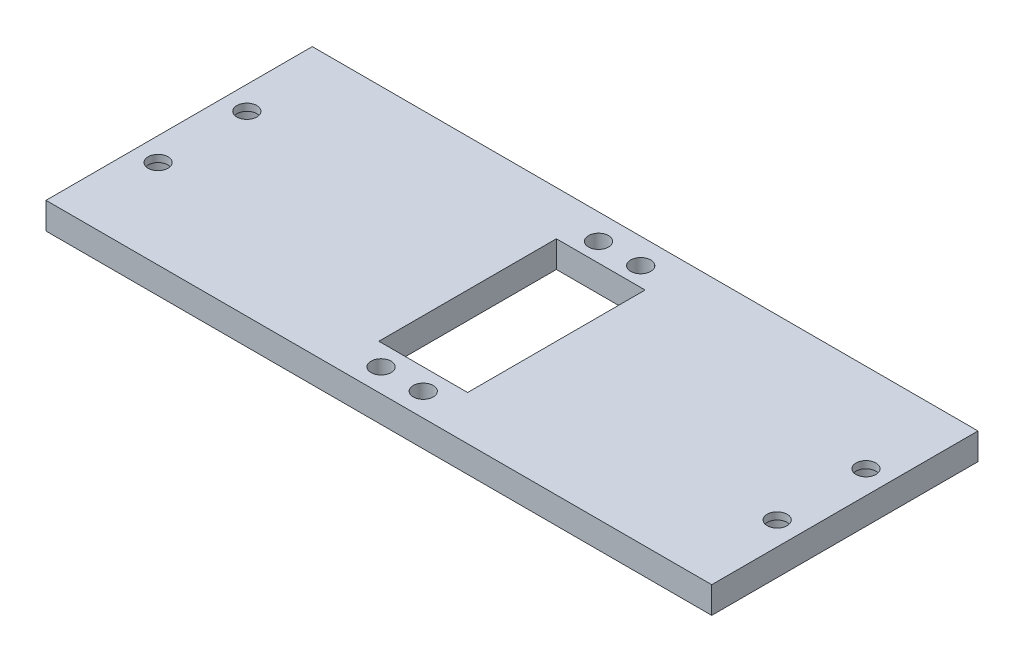
SolidWorks part; units mm, degrees
ref_plane "Front Plane" through (0, 0, 0) normal (0, 0, 1) x (1, 0, 0)
ref_plane "Top Plane" through (0, 0, 0) normal (0, 1, 0) x (1, 0, 0)
ref_plane "Right Plane" through (0, 0, 0) normal (1, 0, 0) x (0, 0, -1)
sketch "Sketch1" plane through (0, 0, 0) normal (0, 1, 0) x (1, 0, 0)
  line L0 (75, -30) -> (-75, -30)
  line L1 (75, -30) -> (75, 30)
  line L2 (75, 30) -> (-75, 30)
  line L3 (-75, -30) -> (-75, 30)
  line L4 (75, -30) -> (-75, 30) construction
  line L5 (75, 30) -> (-75, -30) construction
  line L7 (10, -20) -> (-10, -20)
  line L8 (10, -20) -> (10, 20)
  line L9 (10, 20) -> (-10, 20)
  line L10 (-10, -20) -> (-10, 20)
  line L11 (10, -20) -> (-10, 20) construction
  line L12 (10, 20) -> (-10, -20) construction
  point P0 (0, 0)
  point P20 (0, 0)
  dimension "D1" = 40
  dimension "D2" = 20
  dimension "D3" = 20
  dimension "D4" = 150
  dimension "D5" = 60
extrude "Boss-Extrude1" add sketch "Sketch1" along normal blind 6
ref_plane "Plane1" through (0, 0, 0) normal (-1, 0, 0) x (0, 0, 1)
hole_wizard "CBORE for M4 Hex Socket Head Cap Screw1" positions "Sketch2" profile "Sketch3" counterbore size "M4" standard "DIN" end condition through all
sketch "Sketch2" plane through (0, 0, 178.23) normal (0, -1, 0) x (0, 0, 1)
  point P0 (-168.23, -69.75)
  point P1 (-188.23, -69.75)
sketch "Sketch3" plane through (69.75, 0, 10) normal (1, 0, 0) x (0, 0, -1)
  line L0 (0, 0) -> (0, 6)
  line L1 (0, 6) -> (2.25, 6)
  line L3 (2.25, 6) -> (2.25, 4.4)
  line L4 (2.25, 4.4) -> (4, 4.4)
  line L5 (4, 4.4) -> (4, 0)
  line L7 (4, 0) -> (0, 0)
  line L11 (0, -6.35) -> (0, 107.95) construction
  dimension "Thru Hole Dia." = 4.5
  dimension "Thru Hole Depth" = 6
  dimension "C'Bore Dia." = 8
  dimension "C'Bore Depth" = 4.4
ref_plane "Plane2" through (0, 0, 0) normal (1, 0, 0) x (0, 0, -1)
mirror "Mirror2" about plane through (0, 0, 0) normal (-1, 0, 0) of "CBORE for M4 Hex Socket Head Cap Screw1"
hole_wizard "M4 Clearance Hole1" positions "Sketch4" profile "Sketch5" hole size "M4" standard "DIN"
sketch "Sketch4" plane through (0, 6, 178.23) normal (0, 1, 0) x (0, 0, -1)
  point P0 (153.48, 4.75)
  point P1 (153.48, -4.75)
  point P2 (202.48, -4.75)
  point P3 (202.48, 4.75)
sketch "Sketch5" plane through (-4.75, 6, 24.75) normal (1, 0, 0) x (0, 0, 1)
  line L0 (0, 0) -> (0, 8.499)
  line L1 (0, 8.499) -> (2.25, 8.499)
  line L2 (2.25, 8.499) -> (2.25, 0)
  line L3 (2.25, 0) -> (0, 0)
  line L4 (0, -6.35) -> (0, 107.95) construction
  dimension "Thru Hole Dia." = 4.5
  dimension "Thru Hole Depth" = 8.499
